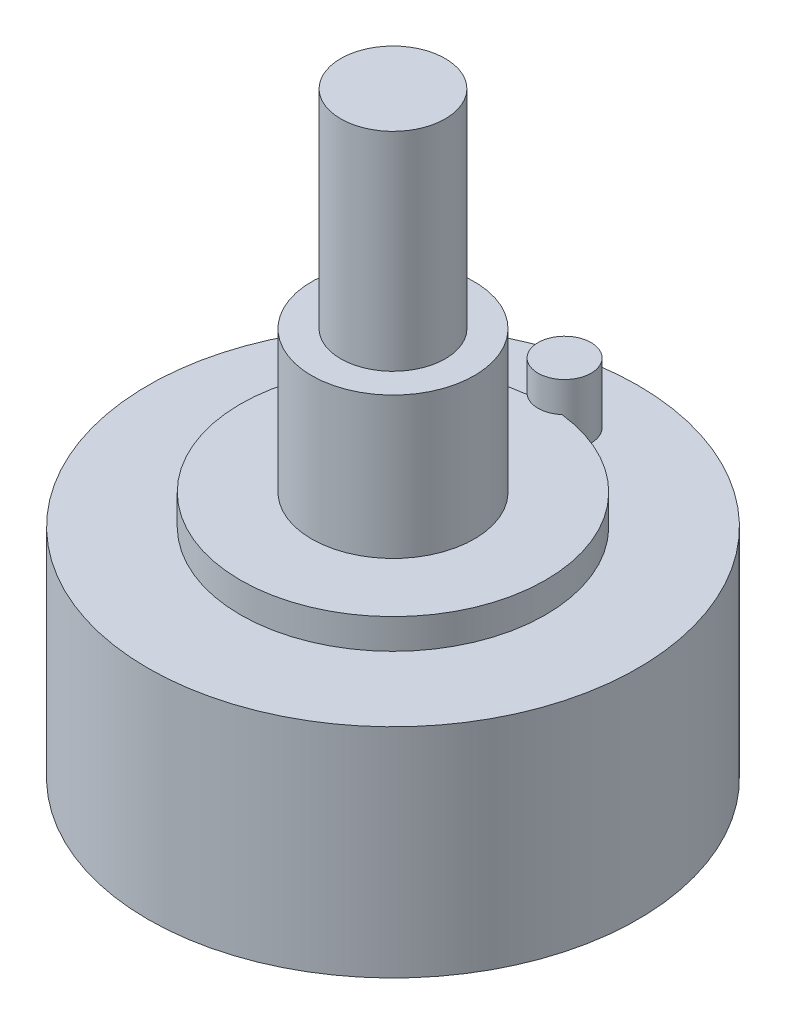
SolidWorks part; units mm, degrees
material "Neutron Star"
ref_plane "Front Plane" through (0, 0, 0) normal (0, 0, 1) x (1, 0, 0)
ref_plane "Top Plane" through (0, 0, 0) normal (0, 1, 0) x (1, 0, 0)
ref_plane "Right Plane" through (0, 0, 0) normal (1, 0, 0) x (0, 0, -1)
sketch "Sketch1" plane through (0, 0, 0) normal (0, 1, 0) x (1, 0, 0)
  circle A0 centre (0, 0) radius 13.85
  dimension "D1" = 27.7
extrude "Boss-Extrude1" add sketch "Sketch1" along normal blind 12.3 contours A0
sketch "Sketch2" plane through (0, 12.3, 0) normal (0, 1, 0) x (1, 0, 0)
  circle A0 centre (0, 0) radius 8.625
  dimension "D1" = 17.25
extrude "Boss-Extrude2" add sketch "Sketch2" along normal blind 1.7
sketch "Sketch3" plane through (0, 14, 0) normal (0, 1, 0) x (1, 0, 0)
  circle A1 centre (0, 0) radius 4.6
  dimension "D1" = 9.2
extrude "Boss-Extrude3" add sketch "Sketch3" along normal blind 8
sketch "Sketch4" plane through (0, 22, 0) normal (0, 1, 0) x (1, 0, 0)
  circle A0 centre (0, 0) radius 2.955
  dimension "D1" = 5.91
extrude "Boss-Extrude4" add sketch "Sketch4" along normal blind 11.75
sketch "Sketch5" plane through (0, 12.3, 0) normal (0, 1, 0) x (1, 0, 0)
  circle A0 centre (0, 0) radius 9.7 construction
  circle A1 centre (0, 9.7) radius 1.5
  dimension "D1" = 19.4
  dimension "D2" = 3
extrude "Boss-Extrude5" add sketch "Sketch5" along normal blind 3.42
